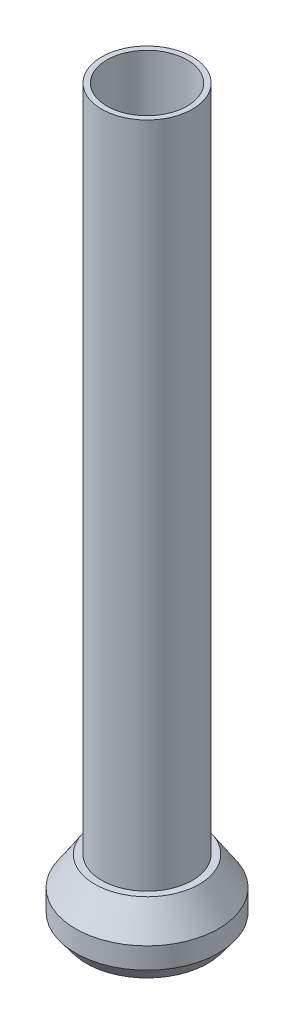
SolidWorks part; units mm, degrees
ref_plane "Front Plane" through (0, 0, 0) normal (0, 0, 1) x (1, 0, 0)
ref_plane "Top Plane" through (0, 0, 0) normal (0, 1, 0) x (1, 0, 0)
ref_plane "Right Plane" through (0, 0, 0) normal (1, 0, 0) x (0, 0, -1)
sketch "Sketch1" plane through (0, 0, 0) normal (0, 1, 0) x (1, 0, 0)
  circle A0 centre (0, 0) radius 12.7
  circle A1 centre (0, 0) radius 11.227
extrude "Boss-Extrude1" add sketch "Sketch1" along normal blind 205
sketch "Sketch2" plane through (0, 0, 0) normal (0, 0, 1) x (1, 0, 0)
  line L0 (0, 0) -> (17, 0)
  line L1 (17, 0) -> (20, 4)
  line L2 (20, 4) -> (20, 9.9)
  line L3 (20, 9.9) -> (14.605, 18)
  line L4 (14.605, 18) -> (0, 18)
  line L5 (0, 18) -> (0, 0)
  line L6 (0, -10) -> (0, 50) construction
revolve "Revolve1" add sketch "Sketch2" angle 360 about L6
